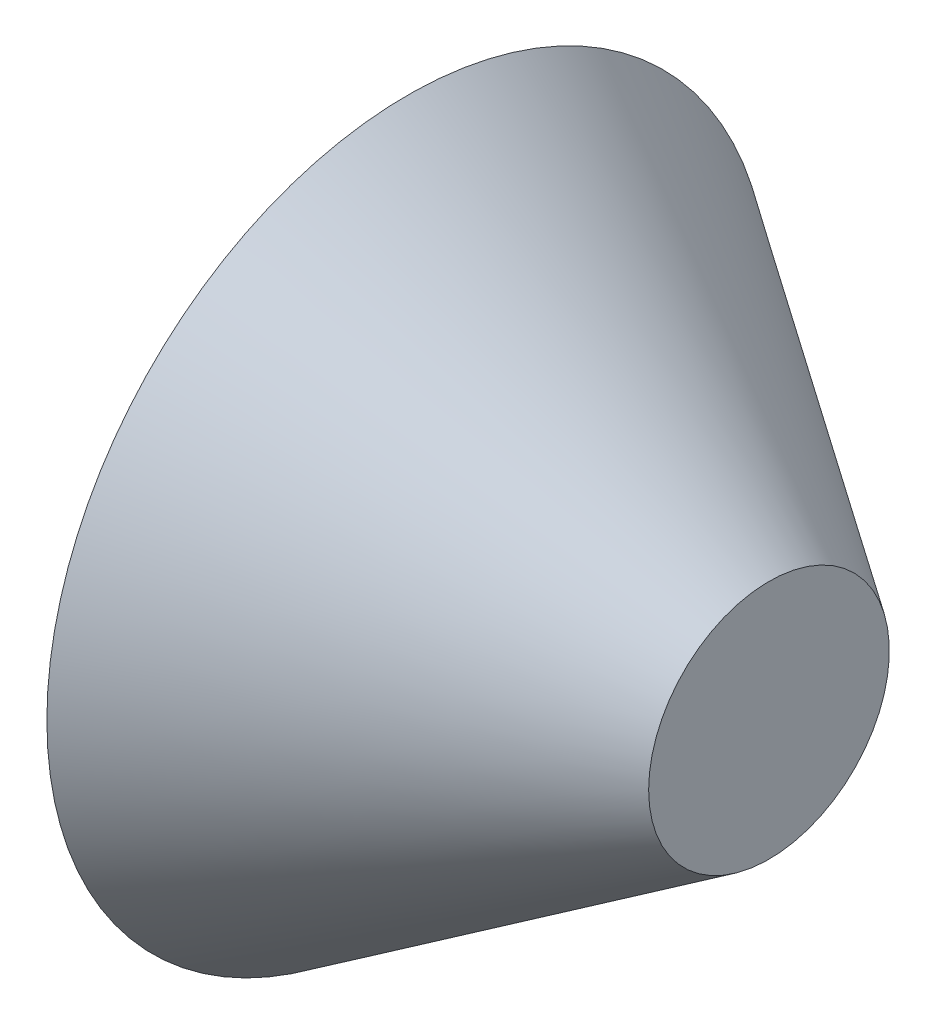
SolidWorks part; units mm, degrees
ref_plane "前视基准面" through (0, 0, 0) normal (0, 0, 1) x (1, 0, 0)
ref_plane "上视基准面" through (0, 0, 0) normal (0, 1, 0) x (1, 0, 0)
ref_plane "右视基准面" through (0, 0, 0) normal (1, 0, 0) x (0, 0, -1)
sketch "草图1" plane through (0, 0, 0) normal (0, 0, 1) x (1, 0, 0)
  line L0 (-1153.6988, 0) -> (56531.2426, 0) construction
  line L1 (0, -1153.6988) -> (0, 56531.2426) construction
  line L6 (-48.2777, 30) -> (-18.2777, 10)
  line L8 (-18.2777, 10) -> (-18.2777, 0)
  line L9 (-18.2777, 0) -> (-20.2777, 0)
  line L10 (-20.2777, 0) -> (-48.2777, 30)
  dimension "D1" = 30
  dimension "D2" = 2
  dimension "D3" = 10
  dimension "D4" = 30
revolve "旋转4" add sketch "草图1" angle 360 mid plane about L0
